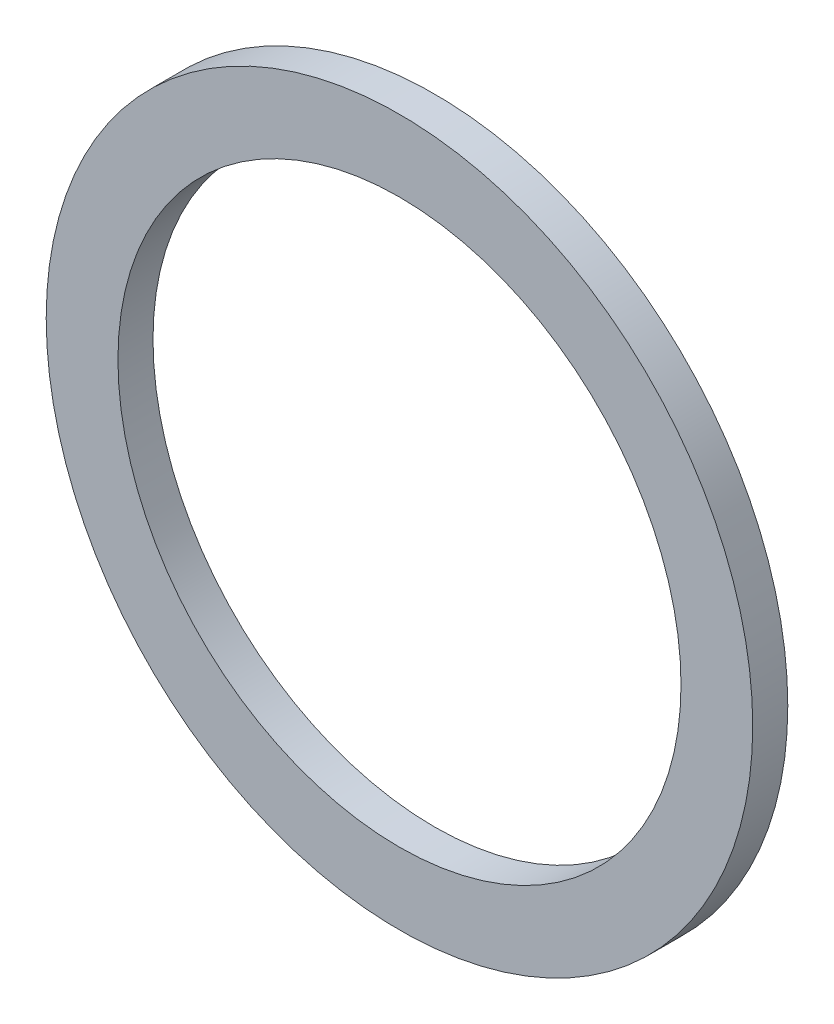
SolidWorks part; units mm, degrees
ref_plane "Front Plane" through (0, 0, 0) normal (0, 0, 1) x (1, 0, 0)
ref_plane "Top Plane" through (0, 0, 0) normal (0, 1, 0) x (1, 0, 0)
ref_plane "Right Plane" through (0, 0, 0) normal (1, 0, 0) x (0, 0, -1)
sketch "Sketch1" plane through (0, 0, 0) normal (0, 0, 1) x (1, 0, 0)
  circle A0 centre (0, 0) radius 32.75
  circle A1 centre (0, 0) radius 26.1
  dimension "D1" = 52.2
  dimension "D2" = 65.5
extrude "Boss-Extrude1" add sketch "Sketch1" along normal blind 3.25
